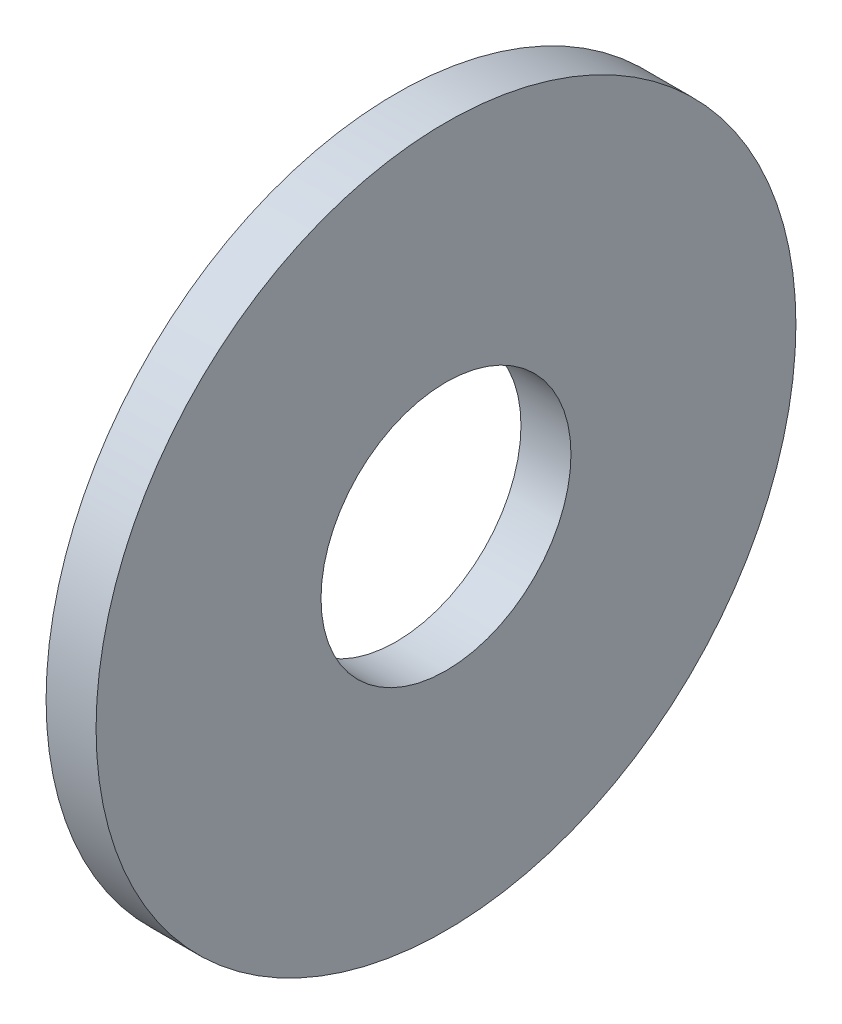
SolidWorks part; units mm, degrees
ref_plane "Front Plane" through (0, 0, 0) normal (0, 0, 1) x (1, 0, 0)
ref_plane "Top Plane" through (0, 0, 0) normal (0, 1, 0) x (1, 0, 0)
ref_plane "Right Plane" through (0, 0, 0) normal (1, 0, 0) x (0, 0, -1)
sketch "Sketch2" plane through (0, 0, 0) normal (1, 0, 0) x (0, 0, -1)
  circle A0 centre (0, 0) radius 7
  circle A1 centre (0, 0) radius 2.5
  dimension "D1" = 14
  dimension "D2" = 5
extrude "Boss-Extrude1" add sketch "Sketch2" along normal blind 1
